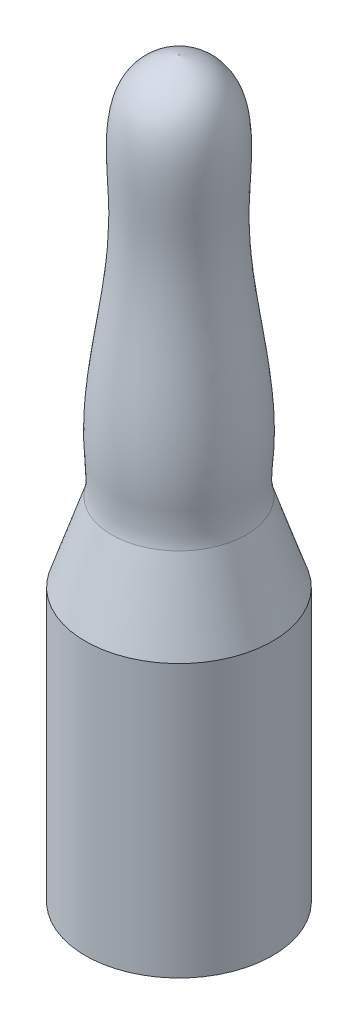
SolidWorks part; units mm, degrees
ref_plane "正面" through (0, 0, 0) normal (0, 0, 1) x (1, 0, 0)
ref_plane "平面" through (0, 0, 0) normal (0, 1, 0) x (1, 0, 0)
ref_plane "右側面" through (0, 0, 0) normal (1, 0, 0) x (0, 0, -1)
sketch "ｽｹｯﾁ3" plane through (0, 0, 0) normal (0, 0, 1) x (1, 0, 0)
  line L0 (0, 0) -> (0, 632)
  line L1 (58, 302.8429) -> (80.7325, 234.7927)
  line L2 (80.7325, 234.7927) -> (80.7325, 0)
  line L3 (80.7325, 0) -> (0, 0)
  spline S0 degree 3 poles (0, 632) (55.1504, 621.1511) (27.5269, 490.952) (65.1282, 385.9522) (55.466, 313.3724) (58, 302.8429) knots 0 0 0 0 0.383406 0.907951 1 1 1 1
  dimension "D1" = 80.7325
  dimension "D2" = 58
  dimension "D5" = 632
  dimension "D6" = 42.8344
  dimension "D7" = 56.6879
  dimension "D3" = 320
revolve "回転1" add sketch "ｽｹｯﾁ3" angle 360 about L0
equation "\"D6@ｽｹｯﾁ3\"=269/(2*3.14)"
equation "\"D7@ｽｹｯﾁ3\"=356/(2*3.14)"
equation "\"D1@ｽｹｯﾁ3\"=507/(3.14*2)"
